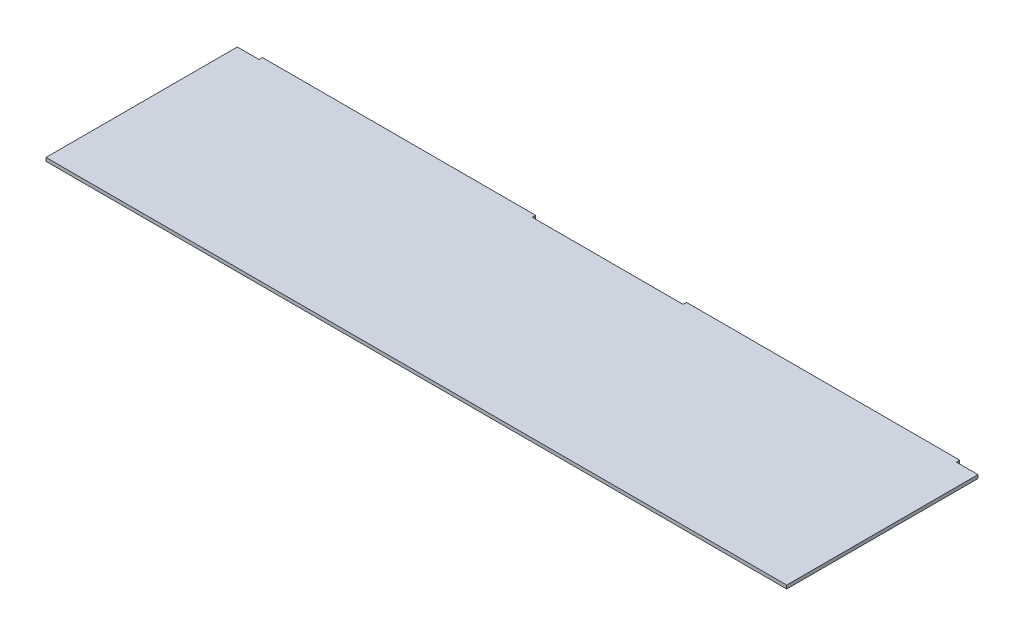
SolidWorks part; units mm, degrees
material "6061-T6 (SS)"
ref_plane "X-Y Datum" through (0, 0, 0) normal (0, 0, 1) x (1, 0, 0)
ref_plane "X-Z Datum" through (0, 0, 0) normal (0, 1, 0) x (1, 0, 0)
ref_plane "Y-Z Datum" through (0, 0, 0) normal (1, 0, 0) x (0, 0, -1)
sketch "Sketch1" plane through (0, 0, 0) normal (0, 1, 0) x (1, 0, 0)
  line L1 (-344.2208, 88.9) -> (344.2208, 88.9)
  line L2 (-344.2208, 88.9) -> (-344.2208, -88.9)
  line L3 (-344.2208, -88.9) -> (344.2208, -88.9)
  line L4 (344.2208, 88.9) -> (344.2208, -88.9)
  line L5 (-344.2208, 88.9) -> (344.2208, -88.9) construction
  line L6 (-344.2208, -88.9) -> (344.2208, 88.9) construction
  point P0 (0, 0)
  dimension "D1" = 688.4416
  dimension "D2" = 177.8
extrude "Boss-Extrude1" add sketch "Sketch1" along normal mid plane 3.175
sketch "Sketch2" plane through (0, 0, -88.9) normal (0, 0, -1) x (-1, 0, 0)
  line L0 (-344.2208, 1.5875) -> (344.2208, 1.5875) construction
  line L1 (-324.0659, 1.5875) -> (-70.0659, 1.5875)
  line L2 (-324.0659, 1.5875) -> (-324.0659, -1.5875)
  line L3 (-324.0659, -1.5875) -> (-70.0659, -1.5875)
  line L4 (-70.0659, 1.5875) -> (-70.0659, -1.5875)
  line L5 (-344.2208, -1.5875) -> (344.2208, -1.5875) construction
  line L6 (0, 55) -> (0, -55) construction
  line L7 (324.0659, -1.5875) -> (70.0659, -1.5875)
  line L8 (324.0659, 1.5875) -> (70.0659, 1.5875)
  line L9 (324.0659, 1.5875) -> (324.0659, -1.5875)
  line L10 (70.0659, 1.5875) -> (70.0659, -1.5875)
extrude "Boss-Extrude2" add sketch "Sketch2" along normal blind 3.175
